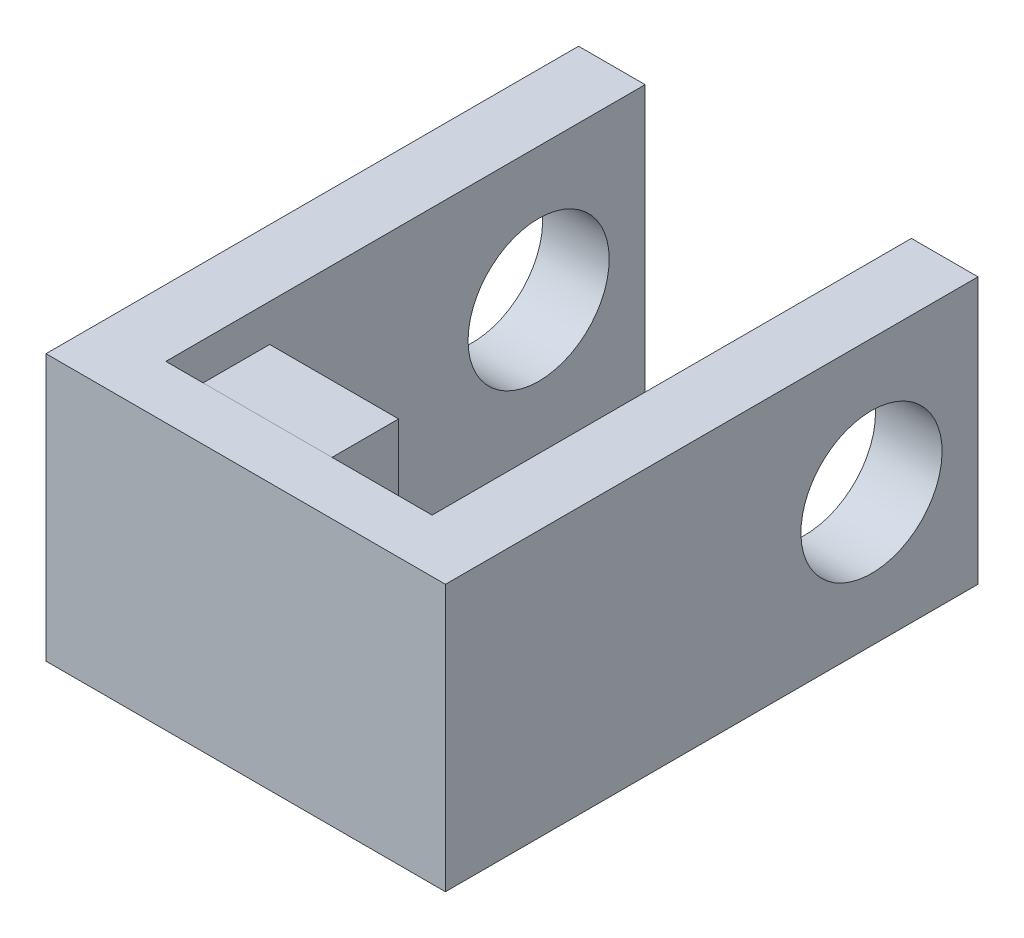
SolidWorks part; units mm, degrees
ref_plane "Front Plane" through (0, 0, 0) normal (0, 0, 1) x (1, 0, 0)
ref_plane "Top Plane" through (0, 0, 0) normal (0, 1, 0) x (1, 0, 0)
ref_plane "Right Plane" through (0, 0, 0) normal (1, 0, 0) x (0, 0, -1)
sketch "Sketch1" plane through (0, 0, 0) normal (0, 0, 1) x (1, 0, 0)
  line L1 (0, 10) -> (15, 10)
  line L2 (0, 10) -> (0, 0)
  line L3 (0, 0) -> (15, 0)
  line L4 (15, 10) -> (15, 0)
  dimension "D1" = 15
  dimension "D2" = 10
extrude "Boss-Extrude1" add sketch "Sketch1" along normal blind 2
sketch "Sketch2" plane through (0, 0, 0) normal (0, 0, -1) x (-1, 0, 0)
  line L0 (-15, 10) -> (0, 10) construction
  line L1 (-15, 0) -> (-12.5, 0)
  line L2 (-15, 0) -> (-15, 10)
  line L3 (-15, 10) -> (-12.5, 10)
  line L4 (-12.5, 0) -> (-12.5, 10)
  line L6 (0, 0) -> (-2.5, 0)
  line L7 (0, 0) -> (0, 10)
  line L8 (0, 10) -> (-2.5, 10)
  line L9 (-2.5, 0) -> (-2.5, 10)
  dimension "D1" = 2.5
  dimension "D2" = 2.5
extrude "Boss-Extrude2" add sketch "Sketch2" along normal blind 18
sketch "Sketch3" plane through (15, 0, 0) normal (1, 0, 0) x (0, 0, -1)
  line L0 (-2, 5) -> (18, 5) construction
  line L1 (-2, 0) -> (-2, 10) construction
  line L2 (18, 10) -> (18, 0) construction
  circle A0 centre (14, 5) radius 2.65
  dimension "D1" = 5.3
  dimension "D2" = 4
extrude "Cut-Extrude1" cut sketch "Sketch3" against normal through all
sketch "Sketch4" plane through (0, 0, 0) normal (0, 0, -1) x (-1, 0, 0)
  line L3 (-8.7416, 10) -> (-8.7416, 0)
  line L4 (-9.3918, 1.2748) -> (-11.0416, 0.6743) construction
  line L5 (-11.0416, 0.6743) -> (-11.0416, 0) construction
  line L9 (-10.8958, 10) -> (-9.3918, 9.4526) construction
  line L10 (-9.2816, 9.2953) -> (-9.2816, 8.9719) construction
  line L11 (-9.3918, 8.8146) -> (-11.0416, 8.2141) construction
  line L12 (-11.0416, 8.2141) -> (-11.0416, 7.5398) construction
  line L13 (-11.0416, 7.5398) -> (-9.3918, 6.9393) construction
  line L14 (-9.2816, 6.7821) -> (-9.2816, 6.4586) construction
  line L15 (-9.3918, 6.3013) -> (-11.0416, 5.7008) construction
  line L16 (-11.0416, 5.7008) -> (-11.0416, 5.0265) construction
  line L17 (-11.0416, 5.0265) -> (-9.3918, 4.426) construction
  line L18 (-9.2816, 4.2688) -> (-9.2816, 3.9453) construction
  line L19 (-9.3918, 3.7881) -> (-11.0416, 3.1876) construction
  line L20 (-11.0416, 3.1876) -> (-11.0416, 2.5133) construction
  line L21 (-11.0416, 2.5133) -> (-9.3918, 1.9128) construction
  line L22 (-9.2816, 1.7555) -> (-9.2816, 1.432) construction
  line L27 (-9.3918, 1.2748) -> (-11.0416, 0.6743)
  line L28 (-11.0416, 0.6743) -> (-11.0416, 0)
  line L32 (-10.8958, 10) -> (-9.3918, 9.4526)
  line L33 (-9.2816, 9.2953) -> (-9.2816, 8.9719)
  line L34 (-9.3918, 8.8146) -> (-11.0416, 8.2141)
  line L35 (-11.0416, 8.2141) -> (-11.0416, 7.5398)
  line L36 (-11.0416, 7.5398) -> (-9.3918, 6.9393)
  line L37 (-9.2816, 6.7821) -> (-9.2816, 6.4586)
  line L38 (-9.3918, 6.3013) -> (-11.0416, 5.7008)
  line L39 (-11.0416, 5.7008) -> (-11.0416, 5.0265)
  line L40 (-11.0416, 5.0265) -> (-9.3918, 4.426)
  line L41 (-9.2816, 4.2688) -> (-9.2816, 3.9453)
  line L42 (-9.3918, 3.7881) -> (-11.0416, 3.1876)
  line L43 (-11.0416, 3.1876) -> (-11.0416, 2.5133)
  line L44 (-11.0416, 2.5133) -> (-9.3918, 1.9128)
  line L45 (-9.2816, 1.7555) -> (-9.2816, 1.432)
  line L46 (-3.9, 10) -> (-8.7416, 10)
  line L47 (-3.9, 0) -> (-8.7416, 0)
  line L48 (-3.9, 10) -> (-3.9, 0)
  line L49 (-2.5, 10) -> (-2.5, 0) construction
  line L50 (-12.5, 10) -> (-2.5, 10) construction
  line L51 (-2.5, 0) -> (-12.5, 0) construction
  arc A0 (-9.2816, 9.2953) -> (-9.3918, 9.4526) centre (-9.449, 9.2953) ccw construction
  arc A1 (-9.3918, 8.8146) -> (-9.2816, 8.9719) centre (-9.449, 8.9719) ccw construction
  arc A2 (-9.2816, 6.7821) -> (-9.3918, 6.9393) centre (-9.449, 6.7821) ccw construction
  arc A3 (-9.3918, 6.3013) -> (-9.2816, 6.4586) centre (-9.449, 6.4586) ccw construction
  arc A4 (-9.2816, 4.2688) -> (-9.3918, 4.426) centre (-9.449, 4.2688) ccw construction
  arc A5 (-9.3918, 3.7881) -> (-9.2816, 3.9453) centre (-9.449, 3.9453) ccw construction
  arc A6 (-9.2816, 1.7555) -> (-9.3918, 1.9128) centre (-9.449, 1.7555) ccw construction
  arc A7 (-9.3918, 1.2748) -> (-9.2816, 1.432) centre (-9.449, 1.432) ccw construction
  arc A8 (-9.2816, 9.2953) -> (-9.3918, 9.4526) centre (-9.449, 9.2953) ccw
  arc A9 (-9.3918, 8.8146) -> (-9.2816, 8.9719) centre (-9.449, 8.9719) ccw
  arc A10 (-9.2816, 6.7821) -> (-9.3918, 6.9393) centre (-9.449, 6.7821) ccw
  arc A11 (-9.3918, 6.3013) -> (-9.2816, 6.4586) centre (-9.449, 6.4586) ccw
  arc A12 (-9.2816, 4.2688) -> (-9.3918, 4.426) centre (-9.449, 4.2688) ccw
  arc A13 (-9.3918, 3.7881) -> (-9.2816, 3.9453) centre (-9.449, 3.9453) ccw
  arc A14 (-9.2816, 1.7555) -> (-9.3918, 1.9128) centre (-9.449, 1.7555) ccw
  arc A15 (-9.3918, 1.2748) -> (-9.2816, 1.432) centre (-9.449, 1.432) ccw
  dimension "D1" = 4.8416
  dimension "D2" = 1.4
extrude "Boss-Extrude3" add sketch "Sketch4" along normal blind 2.5 separate body
